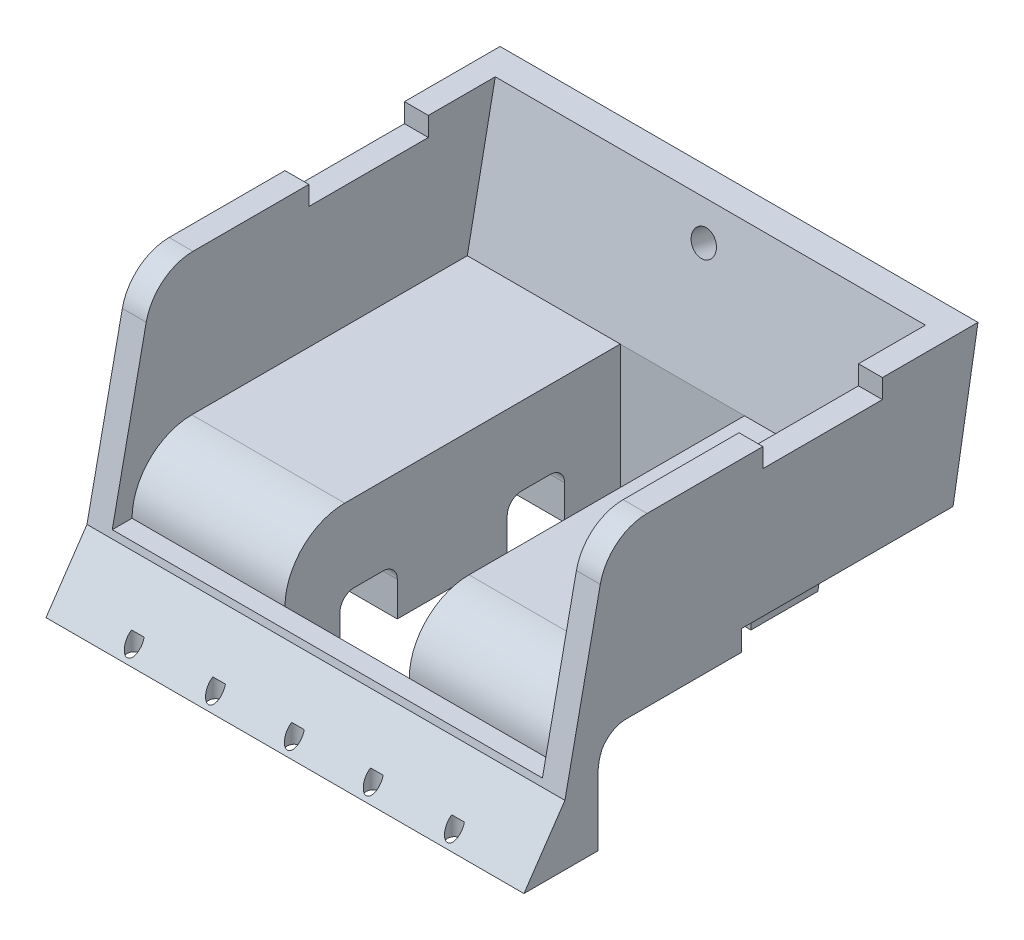
SolidWorks part; units mm, degrees
ref_plane "Alzado" through (0, 0, 0) normal (0, 0, 1) x (1, 0, 0)
ref_plane "Planta" through (0, 0, 0) normal (0, 1, 0) x (1, 0, 0)
ref_plane "Vista lateral" through (0, 0, 0) normal (1, 0, 0) x (0, 0, -1)
sketch "Croquis1" plane through (0, 0, 0) normal (1, 0, 0) x (0, 0, -1)
  line L1 (50, 24) -> (50, 56)
  line L2 (50, 56) -> (-1.5, 56)
  line L6 (57.5, 0) -> (57.5, -7.5) construction
  line L7 (57.5, -7.5) -> (39, -7.5) construction
  line L8 (-35.5, -7.5) -> (-35.5, 0) construction
  line L9 (39, 0) -> (39, 10.5) construction
  line L16 (-9.5, -7.5) -> (-35.5, -7.5) construction
  line L18 (50, 24) -> (-10, 24)
  line L19 (-20, 14) -> (-20, 0)
  line L20 (-20, 0) -> (-35.5, 0)
  line L23 (-35.5, 0) -> (-26.9291, 12.604)
  line L25 (-1.5, 56) -> (-9.7415, 56)
  line L26 (-26.9291, 12.604) -> (-19.5304, 48.0436)
  arc A0 (-10, 24) -> (-20, 14) centre (-10, 14) ccw
  arc A1 (-19.5304, 48.0436) -> (-9.7415, 56) centre (-9.7415, 46) cw
  point P14 (-20, 24)
  point P15 (0, 0)
  point P17 (0, 0)
  point P20 (-17.8694, 56)
  point P21 (-17.6418, 56)
  dimension "D8" = 50
  dimension "D9" = 10
  dimension "D6" = 10
  dimension "D1" = 18.5
  dimension "D2" = 85.5
  dimension "D3" = 70
  dimension "D4" = 7.5
  dimension "D5" = 18
  dimension "D7" = 24
  dimension "D11" = 56
extrude "Saliente-Extruir1" add sketch "Croquis1" along normal blind 100
sketch "Croquis4" plane through (0, 0, 0) normal (0, 0, 1) x (1, 0, 0)
  line L6 (5, 70) -> (5, 0)
  line L7 (5, 0) -> (95, 0)
  line L8 (100, 0) -> (0, 0) construction
  line L9 (95, 0) -> (95, 70)
  line L10 (5, 70) -> (95, 70)
extrude "Cortar-Extruir1" cut sketch "Croquis4" against normal mid plane 88
sketch "Croquis5" plane through (5, 0, 0) normal (1, 0, 0) x (0, 0, -1)
  line L0 (-20, 0) -> (-20, 14)
  line L1 (-10, 24) -> (50, 24)
  line L2 (50, 24) -> (50, 26.5)
  line L3 (50, 24) -> (50, 56) construction
  line L4 (50, 26.5) -> (-10, 26.5)
  line L5 (-22.5, 14) -> (-22.5, 0)
  line L6 (-35.5, 0) -> (-20, 0) construction
  line L7 (-22.5, 0) -> (-20, 0)
  line L8 (10, 26.5) -> (10, 24)
  arc A0 (-20, 14) -> (-10, 24) centre (-10, 14) cw
  arc A1 (-10, 26.5) -> (-22.5, 14) centre (-10, 14) ccw
  dimension "D3" = 10
  dimension "D4" = 12.5
  dimension "D1" = 2.5
  dimension "D2" = 2.5
  dimension "D5" = 40
extrude "Saliente-Extruir2" add sketch "Croquis5" along normal blind 19 contours L7 L0 A0 L1 L2 L4 A1 L5
sketch "Croquis7" plane through (95, 0, 0) normal (-1, 0, 0) x (0, 0, 1)
  line L0 (-10, 26.5) -> (-10, 24) construction
  line L1 (-10, 26.5) -> (-10, 24)
  line L6 (20, 14) -> (20, 0)
  line L7 (-50, 24) -> (10, 24)
  line L8 (-50, 26.5) -> (-50, 24)
  line L9 (10, 26.5) -> (-50, 26.5)
  line L10 (22.5, 0) -> (22.5, 14)
  line L11 (20, 0) -> (22.5, 0)
  line L12 (20, 14) -> (20, 0)
  line L13 (-50, 24) -> (10, 24)
  line L14 (-50, 26.5) -> (-50, 24)
  line L15 (10, 26.5) -> (-50, 26.5)
  line L16 (22.5, 0) -> (22.5, 14)
  line L17 (20, 0) -> (22.5, 0)
  arc A2 (20, 14) -> (10, 24) centre (10, 14) ccw
  arc A3 (22.5, 14) -> (10, 26.5) centre (10, 14) ccw
  arc A4 (20, 14) -> (10, 24) centre (10, 14) ccw
  arc A5 (22.5, 14) -> (10, 26.5) centre (10, 14) ccw
  dimension "D1" = 0
extrude "Saliente-Extruir4" add sketch "Croquis7" along normal blind 19 contours L12 L17 L16 A5 L15 L14 L13 A4
sketch "Croquis10" plane through (24, 0, 0) normal (1, 0, 0) x (0, 0, -1)
  line L11 (10, 0) -> (24, 0)
  line L12 (10, 26.5) -> (10, 24)
  line L13 (10, 0) -> (10, 24)
  line L14 (1, 0) -> (10, 0)
  line L15 (1, 0) -> (1, 7.2)
  line L16 (-2, 10.2) -> (-8, 10.2)
  line L17 (-11, 7.2) -> (-11, 0)
  line L18 (-11, 0) -> (-20, 0)
  line L19 (-22.5, 0) -> (-20, 0)
  line L20 (-22.5, 14) -> (-22.5, 0)
  line L21 (50, 26.5) -> (-10, 26.5)
  line L22 (50, 24) -> (50, 26.5)
  line L23 (50, 0) -> (10, 0) construction
  line L24 (50, 24) -> (50, 0)
  line L25 (50, 0) -> (36, 0)
  line L26 (36, 0) -> (36, 7.2)
  line L27 (33, 10.2) -> (27, 10.2)
  line L28 (24, 7.2) -> (24, 0)
  line L29 (24, 0) -> (10, 0)
  line L30 (30, 0) -> (30, 12) construction
  arc A3 (1, 7.2) -> (-2, 10.2) centre (-2, 7.2) ccw
  arc A4 (-8, 10.2) -> (-11, 7.2) centre (-8, 7.2) ccw
  arc A5 (-10, 26.5) -> (-22.5, 14) centre (-10, 14) ccw
  arc A6 (36, 7.2) -> (33, 10.2) centre (33, 7.2) ccw
  arc A7 (27, 10.2) -> (24, 7.2) centre (27, 7.2) ccw
  point P23 (36, 10.2)
  point P30 (24, 10.2)
  dimension "D4" = 3
  dimension "D1" = 12
  dimension "D2" = 10.2
  dimension "D3" = 6
extrude "Saliente-Extruir7" add sketch "Croquis10" along normal blind 13
sketch "Croquis11" plane through (76, 0, 0) normal (-1, 0, 0) x (0, 0, 1)
  line L0 (-10, 26.5) -> (-10, 24) construction
  line L1 (-10, 0) -> (-10, 24) construction
  line L2 (-1, 0) -> (-10, 0) construction
  line L3 (-1, 0) -> (-1, 7.2) construction
  line L4 (2, 10.2) -> (8, 10.2) construction
  line L5 (11, 7.2) -> (11, 0) construction
  line L6 (11, 0) -> (20, 0) construction
  line L7 (22.5, 0) -> (20, 0) construction
  line L8 (22.5, 14) -> (22.5, 0) construction
  line L9 (-50, 26.5) -> (10, 26.5) construction
  line L10 (-50, 24) -> (-50, 26.5) construction
  line L11 (-50, 24) -> (-50, 0) construction
  line L12 (-50, 0) -> (-36, 0) construction
  line L13 (-36, 0) -> (-36, 7.2) construction
  line L14 (-33, 10.2) -> (-27, 10.2) construction
  line L15 (-24, 7.2) -> (-24, 0) construction
  line L16 (-24, 0) -> (-10, 0) construction
  line L17 (-10, 26.5) -> (-10, 24)
  line L18 (-10, 0) -> (-10, 24)
  line L19 (-1, 0) -> (-10, 0)
  line L20 (-1, 0) -> (-1, 7.2)
  line L21 (2, 10.2) -> (8, 10.2)
  line L22 (11, 7.2) -> (11, 0)
  line L23 (11, 0) -> (20, 0)
  line L24 (22.5, 0) -> (20, 0)
  line L25 (22.5, 14) -> (22.5, 0)
  line L26 (-50, 26.5) -> (10, 26.5)
  line L27 (-50, 24) -> (-50, 26.5)
  line L28 (-50, 24) -> (-50, 0)
  line L29 (-50, 0) -> (-36, 0)
  line L30 (-36, 0) -> (-36, 7.2)
  line L31 (-33, 10.2) -> (-27, 10.2)
  line L32 (-24, 7.2) -> (-24, 0)
  line L33 (-24, 0) -> (-10, 0)
  line L34 (-10, 0) -> (-24, 0) construction
  line L35 (-10, 26.5) -> (-10, 24)
  line L36 (-10, 0) -> (-10, 24)
  line L37 (-10, 0) -> (-24, 0)
  line L38 (-1, 0) -> (-10, 0)
  line L39 (-1, 0) -> (-1, 7.2)
  line L40 (2, 10.2) -> (8, 10.2)
  line L41 (11, 7.2) -> (11, 0)
  line L42 (11, 0) -> (20, 0)
  line L43 (22.5, 0) -> (20, 0)
  line L44 (22.5, 14) -> (22.5, 0)
  line L45 (-50, 26.5) -> (10, 26.5)
  line L46 (-50, 24) -> (-50, 26.5)
  line L47 (-50, 24) -> (-50, 0)
  line L48 (-50, 0) -> (-36, 0)
  line L49 (-36, 0) -> (-36, 7.2)
  line L50 (-33, 10.2) -> (-27, 10.2)
  line L51 (-24, 7.2) -> (-24, 0)
  line L52 (-24, 0) -> (-10, 0)
  arc A0 (2, 10.2) -> (-1, 7.2) centre (2, 7.2) ccw construction
  arc A1 (11, 7.2) -> (8, 10.2) centre (8, 7.2) ccw construction
  arc A2 (22.5, 14) -> (10, 26.5) centre (10, 14) ccw construction
  arc A3 (-33, 10.2) -> (-36, 7.2) centre (-33, 7.2) ccw construction
  arc A4 (-24, 7.2) -> (-27, 10.2) centre (-27, 7.2) ccw construction
  arc A5 (2, 10.2) -> (-1, 7.2) centre (2, 7.2) ccw
  arc A6 (11, 7.2) -> (8, 10.2) centre (8, 7.2) ccw
  arc A7 (22.5, 14) -> (10, 26.5) centre (10, 14) ccw
  arc A8 (-33, 10.2) -> (-36, 7.2) centre (-33, 7.2) ccw
  arc A9 (-24, 7.2) -> (-27, 10.2) centre (-27, 7.2) ccw
  arc A10 (2, 10.2) -> (-1, 7.2) centre (2, 7.2) ccw
  arc A11 (11, 7.2) -> (8, 10.2) centre (8, 7.2) ccw
  arc A12 (22.5, 14) -> (10, 26.5) centre (10, 14) ccw
  arc A13 (-33, 10.2) -> (-36, 7.2) centre (-33, 7.2) ccw
  arc A14 (-24, 7.2) -> (-27, 10.2) centre (-27, 7.2) ccw
  line M57 (10, 26.5) -> (-44, 26.5)
  line M58 (-44, 26.5) -> (-44, 24)
  line M59 (-44, 24) -> (10, 24)
  arc M60 (10, 24) -> (20, 14) centre (10, 14) cw
  line M61 (20, 14) -> (20, 0)
  line M62 (20, 0) -> (22.5, 0)
  line M63 (22.5, 0) -> (22.5, 14)
  arc M64 (22.5, 14) -> (10, 26.5) centre (10, 14) ccw
extrude "Saliente-Extruir28" add sketch "Croquis11" along normal blind 13 contours A6 L22 L23 L18 L19 L20 A5 L21 M61 M60 M59 | A9 L32 L33 L18 L26 L27 L28 L29 L30 A8 L31 M59 M58 | L17 M57 M58 M59 | L17 M57 M59 M60 M61 M62 M63 M64
sketch "Croquis13" plane through (0, 24, 0) normal (0, -1, 0) x (1, 0, 0)
  line L0 (36, -44) -> (64, -44)
  line L1 (64, -44) -> (64, -50)
  line L2 (64, -50) -> (36, -50)
  line L3 (36, -50) -> (36, -44)
extrude "Saliente-Extruir10" add sketch "Croquis13" along normal blind 24
sketch "Croquis15" plane through (0, 0, 0) normal (0, 1, 0) x (1, 0, 0)
  line L2 (0, 50) -> (0, -14.5478) construction
  line L4 (100, 50) -> (0, 50) construction
  circle A1 centre (70, 38.5) radius 1.5
  circle A2 centre (70, 8.5) radius 1.5
  circle A4 centre (70, -18.5) radius 1.5
  circle A13 centre (29, -18.5) radius 1.5
  circle A15 centre (29, 8.5) radius 1.5
  circle A16 centre (29, 38.5) radius 1.5
  dimension "D2" = 3
  dimension "D4" = 3
  dimension "D5" = 41.5
  dimension "D6" = 3
  dimension "D7" = 41
  dimension "D8" = 41
  dimension "D9" = 41
  dimension "D10" = 11.5
  dimension "D14" = 70
  dimension "D3" = 11.5
  dimension "D11" = 41.5
  dimension "D12" = 68.5
  dimension "D13" = 70
  dimension "D15" = 70
  dimension "D17" = 68.5
extrude "Cortar-Extruir2" cut sketch "Croquis15" along normal blind 5
sketch "Croquis16" plane through (100, 0, 0) normal (1, 0, 0) x (0, 0, -1)
  line L1 (10, 24.25) -> (10, 24)
  line L2 (11, 25.25) -> (48, 25.25)
  line L3 (50, 27.25) -> (50, 28.25)
  line L4 (50, 24) -> (50, 56) construction
  line L5 (50, 28.25) -> (50.7337, 28.25)
  line L13 (10, 24) -> (50, 24)
  line L18 (50.7337, 28.25) -> (50.7337, 24)
  line L19 (50.7337, 24) -> (50, 24)
  line L20 (11, 25.25) -> (10, 25.25)
  line L21 (10, 25.25) -> (10, 24.25)
  arc A0 (48, 25.25) -> (50, 27.25) centre (48, 27.25) ccw
  point P24 (50, 25.25)
  dimension "D4" = 2
  dimension "D3" = 3
extrude "Cortar-Extruir3" cut sketch "Croquis16" against normal blind 24
sketch "Croquis17" plane through (100, 0, 0) normal (1, 0, 0) x (0, 0, -1)
  line L1 (7, 20.9442) -> (-14, 20.9442)
  line L2 (-20, 14.9442) -> (-20, 14)
  line L3 (-20, 14) -> (-22.5, 14)
  line L4 (10, 23.9442) -> (10, 20.9442)
  line L5 (10, 20.9442) -> (7, 20.9442)
  line L12 (10, 26.5) -> (10, 24)
  line L21 (10, 26.5) -> (-10, 26.5)
  line L22 (50, 24) -> (50, 26.5)
  line L23 (10, 24) -> (10, 23.9442)
  arc A0 (-14, 20.9442) -> (-20, 14.9442) centre (-14, 14.9442) ccw
  arc A5 (-10, 26.5) -> (-22.5, 14) centre (-10, 14) ccw
  point P13 (10, 20.9442)
  dimension "D1" = 6
extrude "Saliente-Extruir12" add sketch "Croquis17" against normal blind 28
sketch "Croquis18" plane through (76, 0, 0) normal (1, 0, 0) x (0, 0, -1)
  line L0 (50, 0) -> (50, 56)
  line L1 (50, 56) -> (59.5, 56)
  line L2 (59.5, 56) -> (50, 0)
  dimension "D1" = 9.5
extrude "Saliente-Extruir13" add sketch "Croquis18" against normal blind 52
sketch "Croquis19" plane through (100, 0, 0) normal (1, 0, 0) x (0, 0, -1)
  line L0 (48, 25.25) -> (54.2835, 25.25)
  line L1 (50, 0) -> (59.5, 56) construction
  line L2 (54.2835, 25.25) -> (59.5, 56)
  line L3 (59.5, 56) -> (50, 56)
  line L4 (50, 56) -> (50, 27.25)
  arc A0 (50, 27.25) -> (48, 25.25) centre (48, 27.25) cw
extrude "Saliente-Extruir14" add sketch "Croquis19" against normal blind 100
sketch "Croquis20" plane through (0, 0, 0) normal (-1, 0, 0) x (0, 0, 1)
  line L0 (-48, 25.25) -> (-50.7337, 25.25)
  line L9 (-11, 25.25) -> (-48, 25.25)
  line L10 (-10, 25.25) -> (-11, 25.25)
  line L11 (-10, 24.25) -> (-10, 25.25)
  line L12 (-10, 24) -> (-10, 24.25)
  line L13 (-50, 24) -> (-10, 24)
  line L14 (-50.7337, 24) -> (-50, 24)
  line L15 (-50.7337, 28.25) -> (-50.7337, 24)
  line L16 (-50, 28.25) -> (-50.7337, 28.25)
  line L17 (-50, 27.25) -> (-50, 28.25)
  line L18 (-11, 25.25) -> (-48, 25.25)
  line L19 (-10, 25.25) -> (-11, 25.25)
  line L20 (-10, 24.25) -> (-10, 25.25)
  line L21 (-10, 24) -> (-10, 24.25)
  line L22 (-50, 24) -> (-10, 24)
  line L23 (-50.7337, 24) -> (-50, 24)
  line L24 (-50.7337, 25.25) -> (-50.7337, 24)
  arc A1 (-50, 27.25) -> (-48, 25.25) centre (-48, 27.25) ccw
  dimension "D1" = 0
extrude "Cortar-Extruir4" cut sketch "Croquis20" against normal blind 24
sketch "Croquis21" plane through (0, 0, 0) normal (-1, 0, 0) x (0, 0, 1)
  line L0 (-50, 24) -> (-50, 26.5) construction
  line L1 (-50, 24) -> (-50, 26.5)
  line L8 (20, 14) -> (22.5, 14)
  line L9 (20, 14.9442) -> (20, 14)
  line L10 (-7, 20.9442) -> (14, 20.9442)
  line L11 (-10, 20.9442) -> (-7, 20.9442)
  line L12 (-10, 23.9442) -> (-10, 20.9442)
  line L13 (-10, 24) -> (-10, 23.9442)
  line L14 (-10, 26.5) -> (-10, 24)
  line L15 (10, 26.5) -> (-10, 26.5)
  line L16 (20, 14) -> (22.5, 14)
  line L17 (20, 14.9442) -> (20, 14)
  line L18 (-7, 20.9442) -> (14, 20.9442)
  line L19 (-10, 20.9442) -> (-7, 20.9442)
  line L20 (-10, 23.9442) -> (-10, 20.9442)
  line L21 (-10, 24) -> (-10, 23.9442)
  line L22 (-10, 26.5) -> (-10, 24)
  line L23 (10, 26.5) -> (-10, 26.5)
  arc A2 (20, 14.9442) -> (14, 20.9442) centre (14, 14.9442) ccw
  arc A3 (22.5, 14) -> (10, 26.5) centre (10, 14) ccw
  arc A4 (20, 14.9442) -> (14, 20.9442) centre (14, 14.9442) ccw
  arc A5 (22.5, 14) -> (10, 26.5) centre (10, 14) ccw
  dimension "D1" = 0
extrude "Saliente-Extruir15" add sketch "Croquis21" against normal blind 24
ref_plane "Plano1" through (5, 0, 0) normal (1, 0, 0) x (0, 0, -1)
sketch "Croquis23" plane through (5, 0, 0) normal (1, 0, 0) x (0, 0, -1)
  line L0 (44, 56) -> (53.5, 56)
  line L1 (59.5, 56) -> (-9.7415, 56) construction
  line L2 (44, 56) -> (44, 26.5)
  line L4 (47.6513, 26.5) -> (53.5, 56)
  line L7 (44, 26.5) -> (47.6513, 26.5)
  dimension "D1" = 9.5
  dimension "D2" = 1.25
extrude "Cortar-Extruir7" cut sketch "Croquis23" along normal blind 90
ref_plane "Plano3" through (0, 45, 0) normal (0, 1, 0) x (1, 0, 0)
sketch "Croquis37" plane through (0, 56, 0) normal (0, 1, 0) x (1, 0, 0)
  line L6 (95, 39.5) -> (100, 39.5)
  line L7 (95, -10) -> (95, 47.6513) construction
  line L8 (100, 39.5) -> (100, 14.5)
  line L9 (100, 14.5) -> (95, 14.5)
  line L10 (95, -10) -> (95, 47.6513) construction
  line L11 (95, 14.5) -> (95, 39.5)
  line L12 (50, 59.5) -> (50, 8.0478) construction
  line L13 (0, 59.5) -> (100, 59.5) construction
  line L14 (0, 14.5) -> (5, 14.5)
  line L15 (0, 39.5) -> (0, 14.5)
  line L16 (5, 39.5) -> (0, 39.5)
  line L17 (5, 14.5) -> (5, 39.5)
  dimension "D1" = 20
  dimension "D2" = 25
  dimension "D3" = 5
sketch "Croquis39" plane through (0, 0, 0) normal (0, 1, 0) x (1, 0, 0)
  line L1 (5, -30.8) -> (5, 30.8) construction
  line L2 (5, -36.5) -> (5, -26.5)
  line L4 (5, -26.5) -> (5, -22.5)
  line L5 (95, -26.5) -> (95, -36.5)
  line L6 (37, -22.5) -> (5, -22.5) construction
  line L7 (5, -35.5) -> (95, -35.5)
  line L8 (5, -35.5) -> (0, -35.5) construction
  line L9 (5, -22.5) -> (95, -22.5)
  line L10 (95, -22.5) -> (95, -26.5)
extrude "Saliente-Extruir27" add sketch "Croquis39" along normal blind 14
sketch "Croquis40" plane through (95, 0, 0) normal (1, 0, 0) x (0, 0, -1)
  line L1 (-26.6377, 14) -> (-35.5, 14)
  line L2 (-35.5, 14) -> (-35.5, 0)
  line L4 (-26.6377, 14) -> (-26.9291, 12.604)
  line L5 (-26.9291, 12.604) -> (-35.5, 0)
extrude "Cortar-Extruir12" cut sketch "Croquis40" against normal blind 90
sketch "Croquis41" plane through (0, -8.0878, -40.794) normal (0, 0.1945, 0.9809) x (1, 0, 0)
  line L5 (50, 66.5021) -> (50, 56.4959) construction
  circle A0 centre (50, 58.2578) radius 2.6
  point P0 (83.3229, 45.4062)
  point P1 (50, 58.2578)
  dimension "D3" = 5.2
extrude "Cortar-Extruir13" cut sketch "Croquis41" against normal blind 10
sketch "Croquis42" plane through (0, 26.5, 0) normal (0, 1, 0) x (1, 0, 0)
  line L0 (37, 44) -> (37, 47.6513)
  line L1 (95, 47.6513) -> (5, 47.6513) construction
  line L2 (37, 47.6513) -> (63, 47.6513)
  line L3 (63, 47.6513) -> (63, 44)
  line L4 (63, 44) -> (37, 44)
extrude "Cortar-Extruir14" cut sketch "Croquis42" against normal through all
extrude "Cortar-Extruir15" cut sketch "Croquis37" against normal blind 4
sketch "Croquis44" plane through (0, 0, 0) normal (0, -1, 0) x (1, 0, 0)
  line L0 (50, -50) -> (50, 33.5) construction
  line L1 (76, -50) -> (24, -50) construction
  line L2 (100, 35.5) -> (100, 20) construction
  circle A0 centre (50, 33.5) radius 1.5
  circle A1 centre (33.5, 33.5) radius 1.5
  circle A2 centre (16.5, 33.5) radius 1.5
  circle A3 centre (83.5, 33.5) radius 1.5
  circle A4 centre (66.5, 33.5) radius 1.5
  dimension "D2" = 3
  dimension "D3" = 3
  dimension "D4" = 3
  dimension "D1" = 83.5
  dimension "D5" = 83.5
  dimension "D6" = 66.5
extrude "Cortar-Extruir16" cut sketch "Croquis44" against normal blind 4
